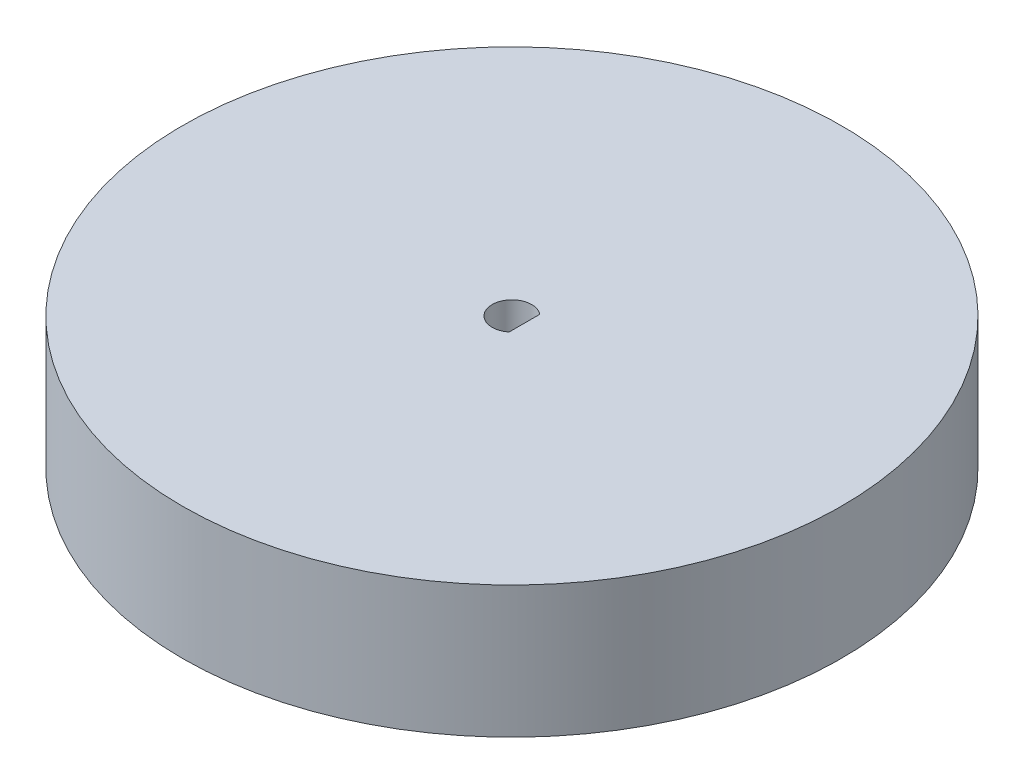
SolidWorks part; units mm, degrees
material "1060 Alloy"
ref_plane "Front Plane" through (0, 0, 0) normal (0, 0, 1) x (1, 0, 0)
ref_plane "Top Plane" through (0, 0, 0) normal (0, 1, 0) x (1, 0, 0)
ref_plane "Right Plane" through (0, 0, 0) normal (1, 0, 0) x (0, 0, -1)
sketch "Sketch2" plane through (0, 0, 0) normal (0, 1, 0) x (1, 0, 0)
  line L0 (0.95, 1.1608) -> (0.95, -1.1608)
  circle A0 centre (0, 0) radius 25
  arc A1 (0.95, 1.1608) -> (0.95, -1.1608) centre (0, 0) ccw
  point P6 (-1.5, 0)
  dimension "D1" = 25
  dimension "D2" = 3
  dimension "D3" = 2.45
extrude "Boss-Extrude1" add sketch "Sketch2" along normal blind 10
